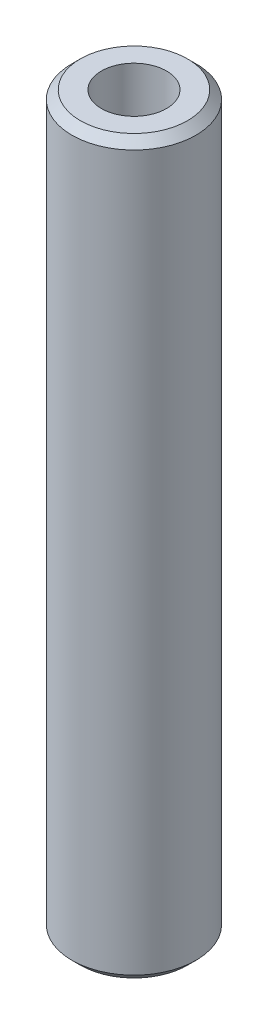
SolidWorks part; units mm, degrees
ref_plane "Front Plane" through (0, 0, 0) normal (0, 0, 1) x (1, 0, 0)
ref_plane "Top Plane" through (0, 0, 0) normal (0, 1, 0) x (1, 0, 0)
ref_plane "Right Plane" through (0, 0, 0) normal (1, 0, 0) x (0, 0, -1)
sketch "Sketch2" plane through (0, 0, 0) normal (0, 1, 0) x (1, 0, 0)
  circle A0 centre (0, 0) radius 2.95
  circle A1 centre (0, 0) radius 1.55
  dimension "D1" = 5.9
  dimension "D2" = 3.1
extrude "Boss-Extrude1" add sketch "Sketch2" along normal blind 34.8
chamfer "Chamfer3" distance 0.4 angle 45 1 edges at (0, 0, 2.95)
chamfer "Chamfer4" distance 0.4 angle 45 1 edges at (0, 34.8, 2.95)
